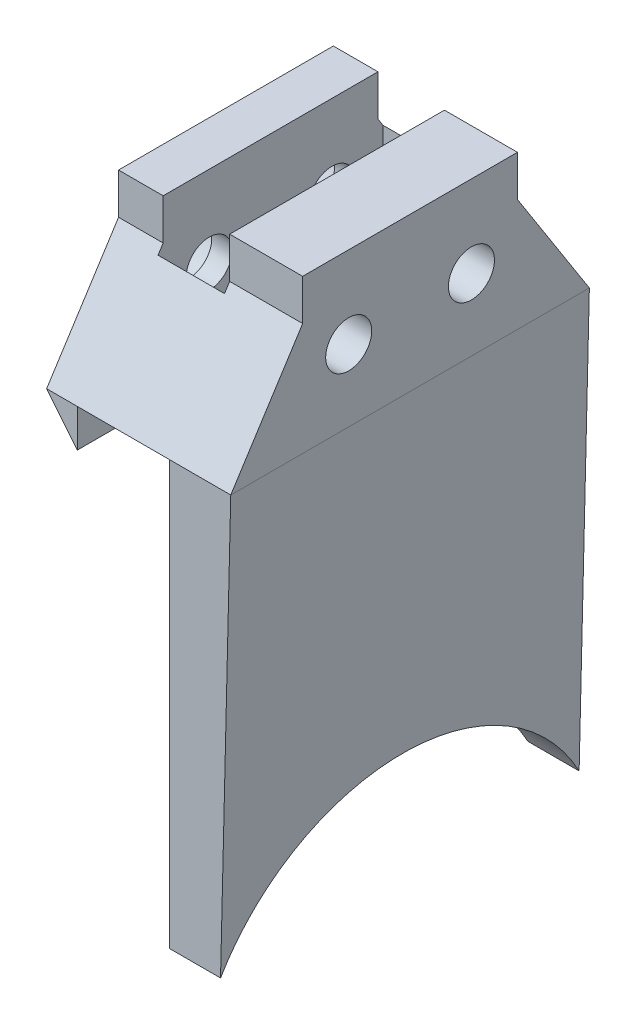
SolidWorks part; units mm, degrees
ref_plane "Front Plane" through (0, 0, 0) normal (0, 0, 1) x (1, 0, 0)
ref_plane "Top Plane" through (0, 0, 0) normal (0, 1, 0) x (1, 0, 0)
ref_plane "Right Plane" through (0, 0, 0) normal (1, 0, 0) x (0, 0, -1)
sketch "Gripper Attachment Base Sketch" plane through (0, 0, 0) normal (0, 0, 1) x (1, 0, 0)
  line L5 (6, 7.5) -> (-6, 7.5)
  line L6 (6, 7.5) -> (6, -7.5)
  line L7 (6, -7.5) -> (-6, -7.5)
  line L8 (-6, 7.5) -> (-6, -7.5)
  line L9 (6, 7.5) -> (-6, -7.5) construction
  line L10 (6, -7.5) -> (-6, 7.5) construction
  point P0 (0, 0)
  dimension "D1" = 12
  dimension "D2" = 15
extrude "Gripper Attachment Base" add sketch "Gripper Attachment Base Sketch" along normal blind 35.0589
sketch "Thickener Base Sketch" plane through (6, 0, 0) normal (1, 0, 0) x (0, 0, -1)
  line L0 (-35.0589, -7.5) -> (-35.0589, 7.5) construction
  line L1 (0, 7.5) -> (-35.0589, 7.5)
  line L2 (0, 7.5) -> (0, -48.8959)
  line L4 (-35.0589, 7.5) -> (-35.0589, -48.8959)
  line L5 (0, -7.5) -> (-35.0589, -7.5) construction
  arc A0 (0, -48.8959) -> (-35.0589, -48.8959) centre (-17.5294, -58.525) ccw
  dimension "D1" = 40
  dimension "D2" = 41.3959
extrude "Thickener Base" add sketch "Thickener Base Sketch" along normal blind 6
sketch "Define Thickness Plane 1" plane through (0, 0, 0) normal (0, 0, 1) x (1, 0, 0)
  line L0 (11, -48.8959) -> (12, -7.5) construction
  line L1 (12, -48.8959) -> (6, -48.8959) construction
  line L2 (12, -48.8959) -> (12, 7.5) construction
  dimension "D1" = 5
sketch "Define Thickness Plane 2" plane through (0, 0, 35.0589) normal (0, 0, 1) x (1, 0, 0)
  line L0 (11, -48.8959) -> (12, -7.5) construction
  line L1 (12, 7.5) -> (12, -48.8959) construction
ref_plane "Thickness Plane" through (12.1741, -0.2941, 0) normal (0.9997, -0.0241, 0) x (0, 0, -1)
sketch "Thickness Cutoff Sketch" plane through (12.1741, -0.2941, 0) normal (0.9997, -0.0241, 0) x (0, 0, -1)
  line L1 (-43.3416, 11.9856) -> (8.1337, 11.9856)
  line L2 (-43.3416, 11.9856) -> (-43.3416, -54.952)
  line L3 (-43.3416, -54.952) -> (8.1337, -54.952)
  line L4 (8.1337, 11.9856) -> (8.1337, -54.952)
extrude "Thickness Cutoff" cut sketch "Thickness Cutoff Sketch" along normal through all
sketch "Excess Material Cutoff Sketch" plane through (0, -520.6815, 0) normal (1, 0, 0) x (0, 0, 1)
  line L3 (7.0294, -528.1815) -> (0, -528.1815)
  line L4 (0, -528.1815) -> (0, -513.1815)
  line L5 (28.0294, -528.1815) -> (35.0589, -528.1815)
  line L6 (35.0589, -528.1815) -> (35.0589, -513.1815)
  line L7 (7.0294, -528.1815) -> (7.0294, -524.1815)
  line L8 (7.0294, -524.1815) -> (0, -513.1815)
  line L9 (28.0294, -528.1815) -> (28.0294, -524.1815)
  line L10 (28.0294, -524.1815) -> (35.0589, -513.1815)
  line L11 (0, -513.1815) -> (0, -471.7856) construction
  line L15 (0, -528.1815) -> (35.0589, -528.1815) construction
  dimension "D1" = 21
  dimension "D2" = 21
  dimension "D3" = 4
extrude "Excess Material Cutoff" cut sketch "Excess Material Cutoff Sketch" along normal through all and the other way through all
sketch "Finger Cavity Cutout Sketch" plane through (0, 7.5, 0) normal (0, 1, 0) x (1, 0, 0)
  line L0 (12, -7.0294) -> (12, -28.0294) construction
  line L1 (-1.6375, -6.5294) -> (4.8625, -6.5294)
  line L2 (-1.6375, -6.5294) -> (-1.6375, -28.5294)
  line L3 (-1.6375, -28.5294) -> (4.8625, -28.5294)
  line L4 (4.8625, -6.5294) -> (4.8625, -28.5294)
  line L5 (-1.6375, -17.5294) -> (12, -17.5294) construction
  point P12 (-1.6375, -17.5294)
  point P15 (1.6125, -6.5294)
  dimension "D1" = 10.3875
  dimension "D2" = 22
  dimension "D3" = 6.5
extrude "Finger Cavity Cutout" cut sketch "Finger Cavity Cutout Sketch" against normal blind 15
sketch "Screw Through-Holes Sketch" plane through (-6, 0, 0) normal (-1, 0, 0) x (0, 0, 1)
  line L0 (28.0294, 7.5) -> (7.0294, 7.5) construction
  line L1 (11.5294, -0.5) -> (23.5294, -0.5) construction
  line L2 (17.5294, -0.5) -> (17.5294, 7.5) construction
  circle A0 centre (11.5294, -0.5) radius 2.25
  circle A1 centre (23.5294, -0.5) radius 2.25
  point P5 (0, 0)
  point P6 (0, 0)
  point P12 (0, 0)
  dimension "D1" = 4.5
  dimension "D2" = 4.5
  dimension "D3" = 12
  dimension "D4" = 8
extrude "Screw Through-Holes" cut sketch "Screw Through-Holes Sketch" against normal through all
sketch "Socket Recesses Sketch" plane through (-6, 0, 0) normal (-1, 0, 0) x (0, 0, 1)
  circle A0 centre (11.5294, -0.5) radius 3.75
  circle A1 centre (23.5294, -0.5) radius 3.75
  circle A2 centre (11.5294, -0.5) radius 2.25 construction
  dimension "D1" = 7.5
  dimension "D2" = 7.5
extrude "Socket Recesses" cut sketch "Socket Recesses Sketch" against normal blind 2.3625
sketch "Shaping to Electronics Plate Sketch" plane through (0, 0, 0) normal (0, 0, 1) x (1, 0, 0)
  line L0 (-6, -7.5) -> (-3, -11.2)
  line L1 (-3, -11.2) -> (-3, -7.5)
  line L2 (-6, -7.5) -> (6, -7.5) construction
  line L3 (-3, -7.5) -> (-6, -7.5)
  point P6 (0, 0)
  point P7 (0, 0)
  point P8 (0, 0)
  dimension "D1" = 3.7
  dimension "D2" = 3
extrude "Shaping to Electronics Plate" add sketch "Shaping to Electronics Plate Sketch" along normal through all
